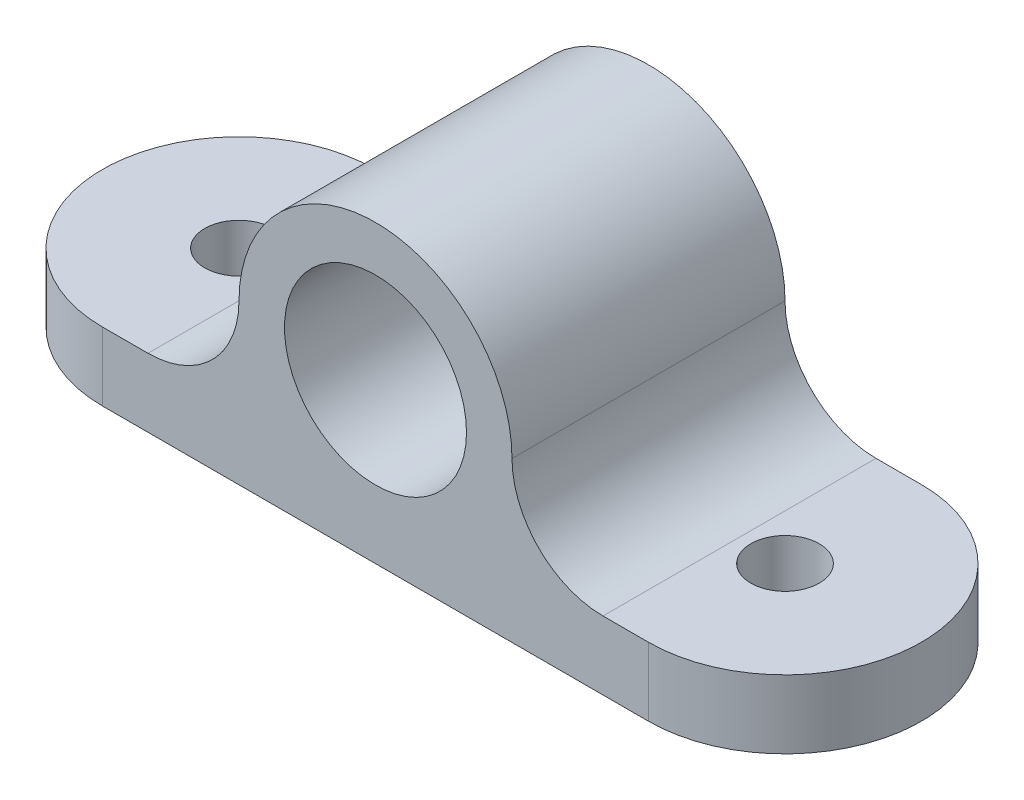
SolidWorks part; units mm, degrees
material "Plain Carbon Steel"
ref_plane "Front Plane" through (0, 0, 0) normal (0, 0, 1) x (1, 0, 0)
ref_plane "Top Plane" through (0, 0, 0) normal (0, 1, 0) x (1, 0, 0)
ref_plane "Right Plane" through (0, 0, 0) normal (1, 0, 0) x (0, 0, -1)
sketch "Sketch1" plane through (0, 0, 0) normal (0, 1, 0) x (1, 0, 0)
  line L0 (0, 19.05) -> (38.1, 19.05)
  line L5 (0, 0) -> (38.1, 0)
  arc A0 (38.1, 0) -> (38.1, 19.05) centre (38.1, 9.525) ccw
  arc A1 (0, 0) -> (0, 19.05) centre (0, 9.525) cw
  dimension "D3" = 9.525
  dimension "D4" = 9.525
  dimension "D1" = 38.1
  dimension "D2" = 19.05
extrude "Boss-Extrude1" add sketch "Sketch1" along normal blind 4.7752
sketch "Sketch3" plane through (0, 4.7752, 0) normal (0, 1, 0) x (1, 0, 0)
  circle A0 centre (38.1, 9.525) radius 2.3876
  arc A1 (38.1, 0) -> (38.1, 19.05) centre (38.1, 9.525) ccw construction
  circle A2 centre (0, 9.525) radius 2.3876
  arc A3 (0, 19.05) -> (0, 0) centre (0, 9.525) ccw construction
  point P2 (0, 0)
  dimension "D1" = 4.7752
  dimension "D2" = 4.7752
extrude "Cut-Extrude1" cut sketch "Sketch3" against normal through all
sketch "Sketch4" plane through (0, 4.7752, 0) normal (0, 1, 0) x (1, 0, 0)
  line L0 (0, 0) -> (38.1, 0) construction
  line L1 (9.525, 0) -> (28.575, 0)
  line L2 (9.525, 0) -> (9.525, 19.05)
  line L3 (9.525, 19.05) -> (28.575, 19.05)
  line L4 (28.575, 0) -> (28.575, 19.05)
  line L5 (38.1, 19.05) -> (0, 19.05) construction
  circle A0 centre (38.1, 9.525) radius 2.3876 construction
  point P8 (19.05, 19.05)
  dimension "D1" = 19.05
  dimension "D2" = 19.05
extrude "Boss-Extrude2" add sketch "Sketch4" along normal blind 15.8496
sketch "Sketch5" plane through (0, 0, 0) normal (0, 0, 1) x (1, 0, 0)
  line L0 (0, 0) -> (38.1, 0) construction
  line L1 (38.1, 4.7752) -> (38.1, 0) construction
  line L2 (28.575, 20.6248) -> (28.575, 4.7752) construction
  line L3 (9.525, 20.6248) -> (9.525, 4.7752) construction
  circle A0 centre (19.05, 11.0998) radius 6.35
  arc A1 (28.575, 11.0998) -> (9.525, 11.0998) centre (19.05, 11.0998) ccw
  line M5 (28.575, 4.7752) -> (28.575, 20.6248)
  line M6 (28.575, 20.6248) -> (9.525, 20.6248)
  line M7 (9.525, 20.6248) -> (9.525, 4.7752)
  dimension "D2" = 12.7
  dimension "D4" = 9.525
  dimension "D1" = 11.0998
  dimension "D3" = 19.05
extrude "Cut-Extrude3" cut sketch "Sketch5" against normal through all contours A1 M5 M6 | A1 M6 M7 | A0
fillet "Fillet1" radius 6.35 1 edges at (28.575, 4.7752, -9.525)
fillet "Fillet2" radius 6.35 1 edges at (9.525, 4.7752, -9.525)
